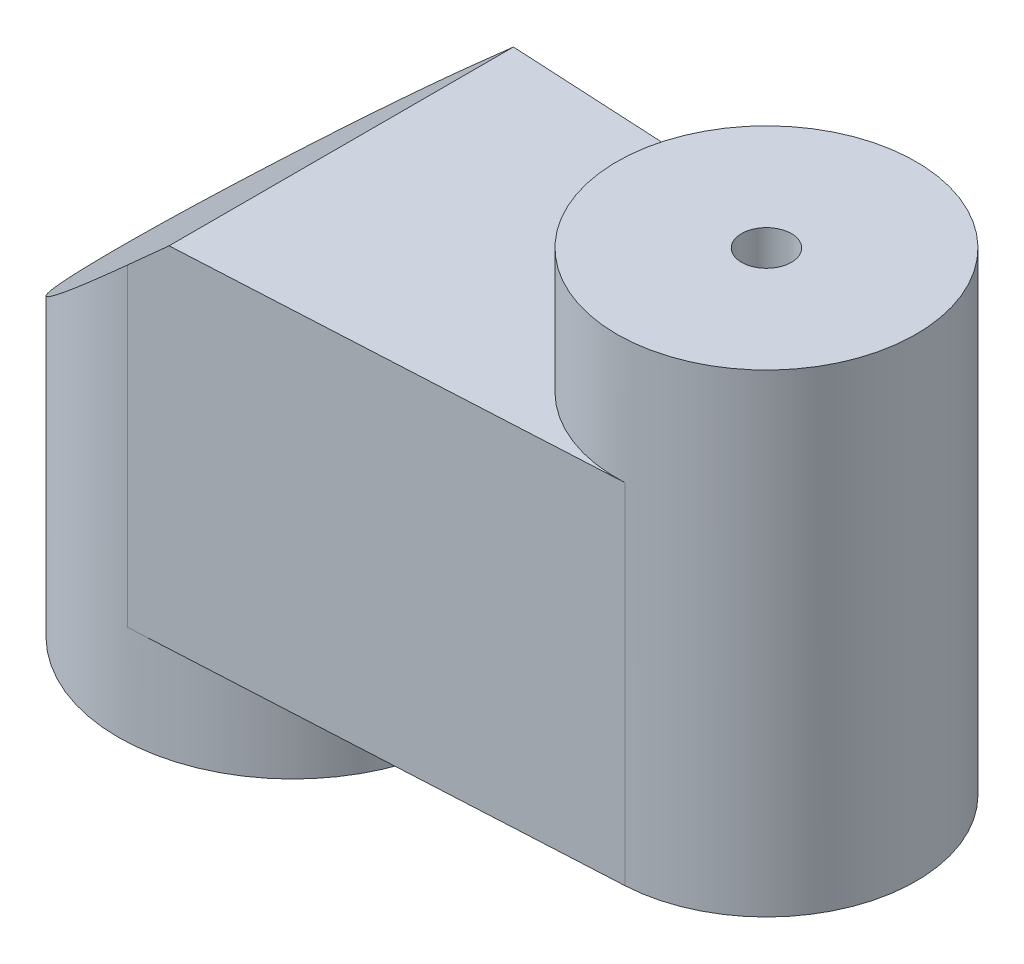
SolidWorks part; units mm, degrees
ref_plane "前视基准面" through (0, 0, 0) normal (0, 0, 1) x (1, 0, 0)
ref_plane "上视基准面" through (0, 0, 0) normal (0, 1, 0) x (1, 0, 0)
ref_plane "右视基准面" through (0, 0, 0) normal (1, 0, 0) x (0, 0, -1)
sketch "草图1" plane through (0, 0, 0) normal (0, 1, 0) x (1, 0, 0)
  circle A0 centre (0, 0) radius 35
  dimension "D1" = 70
extrude "凸台-拉伸1" add sketch "草图1" along normal blind 20
sketch "草图3" plane through (0, 20, 0) normal (0, 1, 0) x (1, 0, 0)
  line L0 (1.8421, 34.9515) -> (96.5789, 29.9584)
  line L1 (1.8421, -34.9515) -> (96.5789, -29.9584)
  arc A0 (1.8421, 34.9515) -> (1.8421, -34.9515) centre (0, 0) ccw
  arc A1 (96.5789, -29.9584) -> (96.5789, 29.9584) centre (95, 0) ccw
  dimension "D1" = 60
  dimension "D2" = 70
  dimension "D3" = 160
extrude "凸台-拉伸2" add sketch "草图3" along normal blind 70
sketch "草图4" plane through (0, 90, 0) normal (0, 1, 0) x (1, 0, 0)
  circle A0 centre (95, 0) radius 30
  dimension "D1" = 60
extrude "凸台-拉伸3" add sketch "草图4" along normal blind 25
sketch "草图5" plane through (0, 0, 0) normal (0, 0, 1) x (1, 0, 0)
  line L0 (9.7214, 90) -> (-35, 50)
  line L1 (1.8421, 90) -> (96.5789, 90) construction
  line L2 (-35, 90) -> (-35, 0) construction
  line L3 (-35, 50) -> (-35, 90)
  line L4 (-35, 90) -> (9.7214, 90)
  line L5 (1.8421, 20) -> (35, 20) construction
  dimension "D1" = 30
  dimension "D2" = 60
extrude "切除-拉伸1" cut sketch "草图5" against normal mid plane 88
sketch "草图6" plane through (0, 115, 0) normal (0, 1, 0) x (1, 0, 0)
  circle A0 centre (95, 0) radius 5
  dimension "D1" = 10
extrude "切除-拉伸2" cut sketch "草图6" against normal through all
